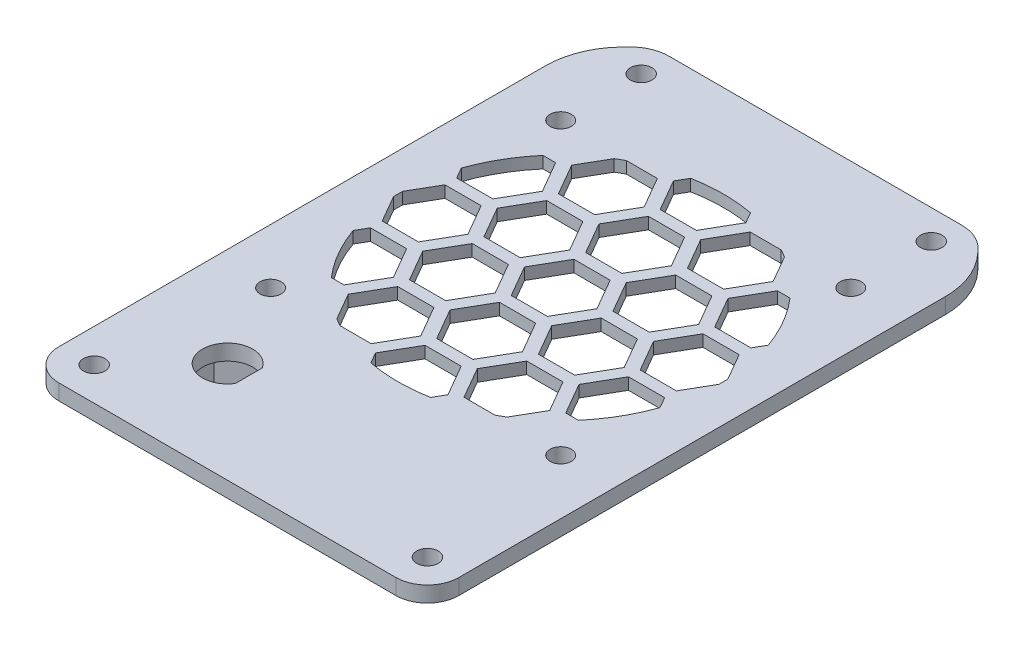
SolidWorks part; units mm, degrees
ref_plane "Front Plane" through (0, 0, 0) normal (0, 0, 1) x (1, 0, 0)
ref_plane "Top Plane" through (0, 0, 0) normal (0, 1, 0) x (1, 0, 0)
ref_plane "Right Plane" through (0, 0, 0) normal (1, 0, 0) x (0, 0, -1)
sketch "Sketch1" plane through (0, -8.5812, 0) normal (0, 1, 0) x (1, 0, 0)
  line L0 (-23.1823, 1.3362) -> (-42.1823, 1.3362)
  line L16 (-54.1823, -73.6638) -> (-11.1823, -73.6638)
  line L17 (-7.1823, -69.6638) -> (-7.1823, -7.6054)
  line L18 (-9.8717, -0.7822) -> (-11.849, 1.3362)
  line L19 (-11.849, 1.3362) -> (-23.1823, 1.3362)
  line L20 (-23.1823, 1.3362) -> (-23.1823, -1.1769)
  line L21 (-23.1823, -1.1769) -> (-10.589, -9.0704)
  line L22 (-9.1823, -11.6123) -> (-9.1823, -59.6638)
  line L23 (-9.1823, -59.6638) -> (-21.1823, -71.6638)
  line L24 (-21.1823, -71.6638) -> (-44.1823, -71.6638)
  line L25 (-44.1823, -71.6638) -> (-56.1823, -59.6638)
  line L26 (-56.1823, -59.6638) -> (-56.1823, -11.6123)
  line L27 (-54.7756, -9.0704) -> (-42.1823, -1.1769)
  line L28 (-42.1823, -1.1769) -> (-42.1823, 1.3362)
  line L29 (-42.1823, 1.3362) -> (-53.5156, 1.3362)
  line L30 (-53.5156, 1.3362) -> (-55.4928, -0.7822)
  line L31 (-58.1823, -7.6054) -> (-58.1823, -69.6638)
  line L32 (-54.1823, -73.6638) -> (-11.1823, -73.6638)
  line L33 (-7.1823, -69.6638) -> (-7.1823, -7.6054)
  line L34 (-9.8717, -0.7822) -> (-11.849, 1.3362)
  line L35 (-11.849, 1.3362) -> (-23.1823, 1.3362)
  line L36 (-23.1823, 1.3362) -> (-23.1823, -1.1769)
  line L37 (-23.1823, -1.1769) -> (-10.589, -9.0704)
  line L38 (-9.1823, -11.6123) -> (-9.1823, -59.6638)
  line L39 (-9.1823, -59.6638) -> (-21.1823, -71.6638)
  line L40 (-21.1823, -71.6638) -> (-44.1823, -71.6638)
  line L41 (-44.1823, -71.6638) -> (-56.1823, -59.6638)
  line L42 (-56.1823, -59.6638) -> (-56.1823, -11.6123)
  line L43 (-54.7756, -9.0704) -> (-42.1823, -1.1769)
  line L44 (-42.1823, -1.1769) -> (-42.1823, 1.3362)
  line L45 (-42.1823, 1.3362) -> (-53.5156, 1.3362)
  line L46 (-53.5156, 1.3362) -> (-55.4928, -0.7822)
  line L47 (-58.1823, -7.6054) -> (-58.1823, -69.6638)
  circle A0 centre (-14.1823, -2.3941) radius 1.375
  circle A1 centre (-51.1823, -2.3941) radius 1.375
  circle A2 centre (-11.4323, -69.4138) radius 1.375
  circle A3 centre (-53.9323, -69.4138) radius 1.375
  arc A6 (-11.1823, -73.6638) -> (-7.1823, -69.6638) centre (-11.1823, -69.6638) ccw
  arc A7 (-7.1823, -7.6054) -> (-9.8717, -0.7822) centre (-17.1823, -7.6054) ccw
  arc A8 (-9.1823, -11.6123) -> (-10.589, -9.0704) centre (-12.1823, -11.6123) ccw
  arc A9 (-54.7756, -9.0704) -> (-56.1823, -11.6123) centre (-53.1823, -11.6123) ccw
  arc A10 (-55.4928, -0.7822) -> (-58.1823, -7.6054) centre (-48.1823, -7.6054) ccw
  arc A11 (-58.1823, -69.6638) -> (-54.1823, -73.6638) centre (-54.1823, -69.6638) ccw
  arc A12 (-11.1823, -73.6638) -> (-7.1823, -69.6638) centre (-11.1823, -69.6638) ccw
  arc A13 (-7.1823, -7.6054) -> (-9.8717, -0.7822) centre (-17.1823, -7.6054) ccw
  arc A14 (-9.1823, -11.6123) -> (-10.589, -9.0704) centre (-12.1823, -11.6123) ccw
  arc A15 (-54.7756, -9.0704) -> (-56.1823, -11.6123) centre (-53.1823, -11.6123) ccw
  arc A16 (-55.4928, -0.7822) -> (-58.1823, -7.6054) centre (-48.1823, -7.6054) ccw
  arc A17 (-58.1823, -69.6638) -> (-54.1823, -73.6638) centre (-54.1823, -69.6638) ccw
  circle M24 centre (-51.1823, -2.3941) radius 2.3
  circle M25 centre (-11.4323, -69.4138) radius 2.3
  circle M26 centre (-53.9323, -69.4138) radius 2.3
  circle M27 centre (-14.1823, -2.3941) radius 2.3
  line M28 (-54.1823, -73.6638) -> (-11.1823, -73.6638)
  arc M29 (-11.1823, -73.6638) -> (-7.1823, -69.6638) centre (-11.1823, -69.6638) ccw
  line M30 (-7.1823, -69.6638) -> (-7.1823, -7.6054)
  arc M31 (-7.1823, -7.6054) -> (-9.8717, -0.7822) centre (-17.1823, -7.6054) ccw
  line M32 (-9.8717, -0.7822) -> (-11.849, 1.3362)
  line M33 (-11.849, 1.3362) -> (-23.1823, 1.3362)
  line M34 (-23.1823, 1.3362) -> (-23.1823, -1.1769)
  line M35 (-23.1823, -1.1769) -> (-10.589, -9.0704)
  arc M36 (-10.589, -9.0704) -> (-9.1823, -11.6123) centre (-12.1823, -11.6123) cw
  line M37 (-9.1823, -11.6123) -> (-9.1823, -59.6638)
  line M38 (-9.1823, -59.6638) -> (-21.1823, -71.6638)
  line M39 (-21.1823, -71.6638) -> (-44.1823, -71.6638)
  line M40 (-44.1823, -71.6638) -> (-56.1823, -59.6638)
  line M41 (-56.1823, -59.6638) -> (-56.1823, -11.6123)
  arc M42 (-56.1823, -11.6123) -> (-54.7756, -9.0704) centre (-53.1823, -11.6123) cw
  line M43 (-54.7756, -9.0704) -> (-42.1823, -1.1769)
  line M44 (-42.1823, -1.1769) -> (-42.1823, 1.3362)
  line M45 (-42.1823, 1.3362) -> (-53.5156, 1.3362)
  line M46 (-53.5156, 1.3362) -> (-55.4928, -0.7822)
  arc M47 (-55.4928, -0.7822) -> (-58.1823, -7.6054) centre (-48.1823, -7.6054) ccw
  line M48 (-58.1823, -7.6054) -> (-58.1823, -69.6638)
  arc M49 (-58.1823, -69.6638) -> (-54.1823, -73.6638) centre (-54.1823, -69.6638) ccw
  dimension "D2" = 2.75
  dimension "D3" = 2.75
  dimension "D4" = 2.75
  dimension "D5" = 2.75
  dimension "D1" = 0
extrude "Boss-Extrude1" add sketch "Sketch1" along normal blind 2 contours M49 M28 M29 M30 M31 M32 M33 M34 M35 M36 M37 M38 M39 M40 M41 M42 M43 M44 M45 M46 M47 M48 M25 M27 M26 M24 | L0 M34 M44 M43 M42 M41 M40 M39 M38 M37 M36 M35 | A0 M27 | A1 M24 | A3 M26 | A2 M25
fillet "Fillet1" radius 5 2 edges at (-11.849, -7.5812, -1.3362) (-53.5156, -7.5812, -1.3362)
sketch "Sketch2" plane through (0, -6.5812, 0) normal (0, 1, 0) x (1, 0, 0)
  circle A1 centre (-32.6823, -31.1638) radius 20.75
  circle A2 centre (-32.6823, -31.1638) radius 20.75
  dimension "D1" = 0
extrude "Cut-Extrude1" cut sketch "Sketch2" against normal through all
sketch "Sketch3" plane through (0, -8.5812, 0) normal (0, -1, 0) x (1, 0, 0)
  circle A2 centre (-32.6823, 31.1638) radius 21.75
  circle A3 centre (-32.6823, 31.1638) radius 21.75
  dimension "D1" = 1
extrude "Cut-Extrude2" cut sketch "Sketch3" against normal blind 0.5
sketch "Sketch4" plane through (0, -6.5812, 0) normal (0, 1, 0) x (1, 0, 0)
  line L0 (-49.1368, -12.1638) -> (-40.9095, -16.9138) construction
  line L1 (-38.6001, -12.9138) -> (-43.2189, -12.9138)
  line L2 (-43.2189, -12.9138) -> (-45.5283, -16.9138)
  line L3 (-45.5283, -16.9138) -> (-43.2189, -20.9138)
  line L4 (-43.2189, -20.9138) -> (-38.6001, -20.9138)
  line L5 (-38.6001, -20.9138) -> (-36.2907, -16.9138)
  line L6 (-36.2907, -16.9138) -> (-38.6001, -12.9138)
  line L7 (-44.518, -12.1638) -> (-46.8274, -8.1638)
  line L8 (-46.8274, -8.1638) -> (-51.4462, -8.1638)
  line L9 (-51.4462, -8.1638) -> (-53.7556, -12.1638)
  line L10 (-53.7556, -12.1638) -> (-51.4462, -16.1638)
  line L11 (-51.4462, -16.1638) -> (-46.8274, -16.1638)
  line L12 (-46.8274, -16.1638) -> (-44.518, -12.1638)
  line L13 (-22.1456, -12.9138) -> (-26.7644, -12.9138)
  line L14 (-26.7644, -12.9138) -> (-29.0738, -16.9138)
  line L15 (-29.0738, -16.9138) -> (-26.7644, -20.9138)
  line L16 (-26.7644, -20.9138) -> (-22.1456, -20.9138)
  line L17 (-22.1456, -20.9138) -> (-19.8362, -16.9138)
  line L18 (-19.8362, -16.9138) -> (-22.1456, -12.9138)
  line L19 (-28.0635, -12.1638) -> (-30.3729, -8.1638)
  line L20 (-34.9917, -8.1638) -> (-37.3011, -12.1638)
  line L21 (-37.3011, -12.1638) -> (-34.9917, -16.1638)
  line L22 (-34.9917, -16.1638) -> (-30.3729, -16.1638)
  line L23 (-30.3729, -16.1638) -> (-28.0635, -12.1638)
  line L24 (-32.6823, -12.1638) -> (-24.455, -16.9138) construction
  line L25 (-30.3729, -8.1638) -> (-34.9917, -8.1638)
  line L26 (-5.6912, -12.9138) -> (-10.31, -12.9138)
  line L27 (-10.31, -12.9138) -> (-12.6194, -16.9138)
  line L28 (-12.6194, -16.9138) -> (-10.31, -20.9138)
  line L29 (-10.31, -20.9138) -> (-5.6912, -20.9138)
  line L30 (-5.6912, -20.9138) -> (-3.3818, -16.9138)
  line L31 (-3.3818, -16.9138) -> (-5.6912, -12.9138)
  line L32 (-11.609, -12.1638) -> (-13.9184, -8.1638)
  line L33 (-18.5372, -8.1638) -> (-20.8466, -12.1638)
  line L34 (-20.8466, -12.1638) -> (-18.5372, -16.1638)
  line L35 (-18.5372, -16.1638) -> (-13.9184, -16.1638)
  line L36 (-13.9184, -16.1638) -> (-11.609, -12.1638)
  line L37 (-16.2278, -12.1638) -> (-8.0006, -16.9138) construction
  line L38 (-13.9184, -8.1638) -> (-18.5372, -8.1638)
  line L39 (-22.1456, -22.4138) -> (-26.7644, -22.4138)
  line L40 (-26.7644, -22.4138) -> (-29.0738, -26.4138)
  line L41 (-29.0738, -26.4138) -> (-26.7644, -30.4138)
  line L42 (-26.7644, -30.4138) -> (-22.1456, -30.4138)
  line L43 (-22.1456, -30.4138) -> (-19.8362, -26.4138)
  line L44 (-19.8362, -26.4138) -> (-22.1456, -22.4138)
  line L45 (-28.0635, -21.6638) -> (-30.3729, -17.6638)
  line L46 (-34.9917, -17.6638) -> (-37.3011, -21.6638)
  line L47 (-37.3011, -21.6638) -> (-34.9917, -25.6638)
  line L48 (-34.9917, -25.6638) -> (-30.3729, -25.6638)
  line L49 (-30.3729, -25.6638) -> (-28.0635, -21.6638)
  line L50 (-32.6823, -21.6638) -> (-24.455, -26.4138) construction
  line L51 (-30.3729, -17.6638) -> (-34.9917, -17.6638)
  line L52 (-5.6912, -22.4138) -> (-10.31, -22.4138)
  line L53 (-10.31, -22.4138) -> (-12.6194, -26.4138)
  line L54 (-12.6194, -26.4138) -> (-10.31, -30.4138)
  line L55 (-10.31, -30.4138) -> (-5.6912, -30.4138)
  line L56 (-5.6912, -30.4138) -> (-3.3818, -26.4138)
  line L57 (-3.3818, -26.4138) -> (-5.6912, -22.4138)
  line L58 (-11.609, -21.6638) -> (-13.9184, -17.6638)
  line L59 (-18.5372, -17.6638) -> (-20.8466, -21.6638)
  line L60 (-20.8466, -21.6638) -> (-18.5372, -25.6638)
  line L61 (-18.5372, -25.6638) -> (-13.9184, -25.6638)
  line L62 (-13.9184, -25.6638) -> (-11.609, -21.6638)
  line L63 (-16.2278, -21.6638) -> (-8.0006, -26.4138) construction
  line L64 (-13.9184, -17.6638) -> (-18.5372, -17.6638)
  line L65 (-22.1456, -31.9138) -> (-26.7644, -31.9138)
  line L66 (-26.7644, -31.9138) -> (-29.0738, -35.9138)
  line L67 (-29.0738, -35.9138) -> (-26.7644, -39.9138)
  line L68 (-26.7644, -39.9138) -> (-22.1456, -39.9138)
  line L69 (-22.1456, -39.9138) -> (-19.8362, -35.9138)
  line L70 (-19.8362, -35.9138) -> (-22.1456, -31.9138)
  line L71 (-28.0635, -31.1638) -> (-30.3729, -27.1638)
  line L72 (-34.9917, -27.1638) -> (-37.3011, -31.1638)
  line L73 (-37.3011, -31.1638) -> (-34.9917, -35.1638)
  line L74 (-34.9917, -35.1638) -> (-30.3729, -35.1638)
  line L75 (-30.3729, -35.1638) -> (-28.0635, -31.1638)
  line L76 (-32.6823, -31.1638) -> (-24.455, -35.9138) construction
  line L77 (-30.3729, -27.1638) -> (-34.9917, -27.1638)
  line L78 (-5.6912, -31.9138) -> (-10.31, -31.9138)
  line L79 (-10.31, -31.9138) -> (-12.6194, -35.9138)
  line L80 (-12.6194, -35.9138) -> (-10.31, -39.9138)
  line L81 (-10.31, -39.9138) -> (-5.6912, -39.9138)
  line L82 (-5.6912, -39.9138) -> (-3.3818, -35.9138)
  line L83 (-3.3818, -35.9138) -> (-5.6912, -31.9138)
  line L84 (-11.609, -31.1638) -> (-13.9184, -27.1638)
  line L85 (-18.5372, -27.1638) -> (-20.8466, -31.1638)
  line L86 (-20.8466, -31.1638) -> (-18.5372, -35.1638)
  line L87 (-18.5372, -35.1638) -> (-13.9184, -35.1638)
  line L88 (-13.9184, -35.1638) -> (-11.609, -31.1638)
  line L89 (-16.2278, -31.1638) -> (-8.0006, -35.9138) construction
  line L90 (-13.9184, -27.1638) -> (-18.5372, -27.1638)
  line L91 (-22.1456, -41.4138) -> (-26.7644, -41.4138)
  line L92 (-26.7644, -41.4138) -> (-29.0738, -45.4138)
  line L93 (-29.0738, -45.4138) -> (-26.7644, -49.4138)
  line L94 (-26.7644, -49.4138) -> (-22.1456, -49.4138)
  line L95 (-22.1456, -49.4138) -> (-19.8362, -45.4138)
  line L96 (-19.8362, -45.4138) -> (-22.1456, -41.4138)
  line L97 (-28.0635, -40.6638) -> (-30.3729, -36.6638)
  line L98 (-34.9917, -36.6638) -> (-37.3011, -40.6638)
  line L99 (-37.3011, -40.6638) -> (-34.9917, -44.6638)
  line L100 (-34.9917, -44.6638) -> (-30.3729, -44.6638)
  line L101 (-30.3729, -44.6638) -> (-28.0635, -40.6638)
  line L102 (-32.6823, -40.6638) -> (-24.455, -45.4138) construction
  line L103 (-30.3729, -36.6638) -> (-34.9917, -36.6638)
  line L104 (-5.6912, -41.4138) -> (-10.31, -41.4138)
  line L105 (-10.31, -41.4138) -> (-12.6194, -45.4138)
  line L106 (-12.6194, -45.4138) -> (-10.31, -49.4138)
  line L107 (-10.31, -49.4138) -> (-5.6912, -49.4138)
  line L108 (-5.6912, -49.4138) -> (-3.3818, -45.4138)
  line L109 (-3.3818, -45.4138) -> (-5.6912, -41.4138)
  line L110 (-11.609, -40.6638) -> (-13.9184, -36.6638)
  line L111 (-18.5372, -36.6638) -> (-20.8466, -40.6638)
  line L112 (-20.8466, -40.6638) -> (-18.5372, -44.6638)
  line L113 (-18.5372, -44.6638) -> (-13.9184, -44.6638)
  line L114 (-13.9184, -44.6638) -> (-11.609, -40.6638)
  line L115 (-16.2278, -40.6638) -> (-8.0006, -45.4138) construction
  line L116 (-13.9184, -36.6638) -> (-18.5372, -36.6638)
  line L117 (-22.1456, -50.9138) -> (-26.7644, -50.9138)
  line L118 (-26.7644, -50.9138) -> (-29.0738, -54.9138)
  line L119 (-29.0738, -54.9138) -> (-26.7644, -58.9138)
  line L120 (-26.7644, -58.9138) -> (-22.1456, -58.9138)
  line L121 (-22.1456, -58.9138) -> (-19.8362, -54.9138)
  line L122 (-19.8362, -54.9138) -> (-22.1456, -50.9138)
  line L123 (-28.0635, -50.1638) -> (-30.3729, -46.1638)
  line L124 (-34.9917, -46.1638) -> (-37.3011, -50.1638)
  line L125 (-37.3011, -50.1638) -> (-34.9917, -54.1638)
  line L126 (-34.9917, -54.1638) -> (-30.3729, -54.1638)
  line L127 (-30.3729, -54.1638) -> (-28.0635, -50.1638)
  line L128 (-32.6823, -50.1638) -> (-24.455, -54.9138) construction
  line L129 (-30.3729, -46.1638) -> (-34.9917, -46.1638)
  line L130 (-5.6912, -50.9138) -> (-10.31, -50.9138)
  line L131 (-10.31, -50.9138) -> (-12.6194, -54.9138)
  line L132 (-12.6194, -54.9138) -> (-10.31, -58.9138)
  line L133 (-10.31, -58.9138) -> (-5.6912, -58.9138)
  line L134 (-5.6912, -58.9138) -> (-3.3818, -54.9138)
  line L135 (-3.3818, -54.9138) -> (-5.6912, -50.9138)
  line L136 (-11.609, -50.1638) -> (-13.9184, -46.1638)
  line L137 (-18.5372, -46.1638) -> (-20.8466, -50.1638)
  line L138 (-20.8466, -50.1638) -> (-18.5372, -54.1638)
  line L139 (-18.5372, -54.1638) -> (-13.9184, -54.1638)
  line L140 (-13.9184, -54.1638) -> (-11.609, -50.1638)
  line L141 (-16.2278, -50.1638) -> (-8.0006, -54.9138) construction
  line L142 (-13.9184, -46.1638) -> (-18.5372, -46.1638)
  line L143 (-38.6001, -22.4138) -> (-43.2189, -22.4138)
  line L144 (-43.2189, -22.4138) -> (-45.5283, -26.4138)
  line L145 (-45.5283, -26.4138) -> (-43.2189, -30.4138)
  line L146 (-43.2189, -30.4138) -> (-38.6001, -30.4138)
  line L147 (-38.6001, -30.4138) -> (-36.2907, -26.4138)
  line L148 (-36.2907, -26.4138) -> (-38.6001, -22.4138)
  line L149 (-44.518, -21.6638) -> (-46.8274, -17.6638)
  line L150 (-51.4462, -17.6638) -> (-53.7556, -21.6638)
  line L151 (-53.7556, -21.6638) -> (-51.4462, -25.6638)
  line L152 (-51.4462, -25.6638) -> (-46.8274, -25.6638)
  line L153 (-46.8274, -25.6638) -> (-44.518, -21.6638)
  line L154 (-49.1368, -21.6638) -> (-40.9095, -26.4138) construction
  line L155 (-46.8274, -17.6638) -> (-51.4462, -17.6638)
  line L156 (-38.6001, -31.9138) -> (-43.2189, -31.9138)
  line L157 (-43.2189, -31.9138) -> (-45.5283, -35.9138)
  line L158 (-45.5283, -35.9138) -> (-43.2189, -39.9138)
  line L159 (-43.2189, -39.9138) -> (-38.6001, -39.9138)
  line L160 (-38.6001, -39.9138) -> (-36.2907, -35.9138)
  line L161 (-36.2907, -35.9138) -> (-38.6001, -31.9138)
  line L162 (-44.518, -31.1638) -> (-46.8274, -27.1638)
  line L163 (-51.4462, -27.1638) -> (-53.7556, -31.1638)
  line L164 (-53.7556, -31.1638) -> (-51.4462, -35.1638)
  line L165 (-51.4462, -35.1638) -> (-46.8274, -35.1638)
  line L166 (-46.8274, -35.1638) -> (-44.518, -31.1638)
  line L167 (-49.1368, -31.1638) -> (-40.9095, -35.9138) construction
  line L168 (-46.8274, -27.1638) -> (-51.4462, -27.1638)
  line L169 (-38.6001, -41.4138) -> (-43.2189, -41.4138)
  line L170 (-43.2189, -41.4138) -> (-45.5283, -45.4138)
  line L171 (-45.5283, -45.4138) -> (-43.2189, -49.4138)
  line L172 (-43.2189, -49.4138) -> (-38.6001, -49.4138)
  line L173 (-38.6001, -49.4138) -> (-36.2907, -45.4138)
  line L174 (-36.2907, -45.4138) -> (-38.6001, -41.4138)
  line L175 (-44.518, -40.6638) -> (-46.8274, -36.6638)
  line L176 (-51.4462, -36.6638) -> (-53.7556, -40.6638)
  line L177 (-53.7556, -40.6638) -> (-51.4462, -44.6638)
  line L178 (-51.4462, -44.6638) -> (-46.8274, -44.6638)
  line L179 (-46.8274, -44.6638) -> (-44.518, -40.6638)
  line L180 (-49.1368, -40.6638) -> (-40.9095, -45.4138) construction
  line L181 (-46.8274, -36.6638) -> (-51.4462, -36.6638)
  line L182 (-38.6001, -50.9138) -> (-43.2189, -50.9138)
  line L183 (-43.2189, -50.9138) -> (-45.5283, -54.9138)
  line L184 (-45.5283, -54.9138) -> (-43.2189, -58.9138)
  line L185 (-43.2189, -58.9138) -> (-38.6001, -58.9138)
  line L186 (-38.6001, -58.9138) -> (-36.2907, -54.9138)
  line L187 (-36.2907, -54.9138) -> (-38.6001, -50.9138)
  line L188 (-44.518, -50.1638) -> (-46.8274, -46.1638)
  line L189 (-51.4462, -46.1638) -> (-53.7556, -50.1638)
  line L190 (-53.7556, -50.1638) -> (-51.4462, -54.1638)
  line L191 (-51.4462, -54.1638) -> (-46.8274, -54.1638)
  line L192 (-46.8274, -54.1638) -> (-44.518, -50.1638)
  line L193 (-49.1368, -50.1638) -> (-40.9095, -54.9138) construction
  line L194 (-46.8274, -46.1638) -> (-51.4462, -46.1638)
  circle A0 centre (-40.9095, -16.9138) radius 4 construction
  circle A1 centre (-49.1368, -12.1638) radius 4 construction
  circle A2 centre (-24.455, -16.9138) radius 4 construction
  circle A3 centre (-32.6823, -12.1638) radius 4 construction
  circle A4 centre (-8.0006, -16.9138) radius 4 construction
  circle A5 centre (-16.2278, -12.1638) radius 4 construction
  circle A6 centre (-24.455, -26.4138) radius 4 construction
  circle A7 centre (-32.6823, -21.6638) radius 4 construction
  circle A8 centre (-8.0006, -26.4138) radius 4 construction
  circle A9 centre (-16.2278, -21.6638) radius 4 construction
  circle A10 centre (-24.455, -35.9138) radius 4 construction
  circle A11 centre (-32.6823, -31.1638) radius 4 construction
  circle A12 centre (-8.0006, -35.9138) radius 4 construction
  circle A13 centre (-16.2278, -31.1638) radius 4 construction
  circle A14 centre (-24.455, -45.4138) radius 4 construction
  circle A15 centre (-32.6823, -40.6638) radius 4 construction
  circle A16 centre (-8.0006, -45.4138) radius 4 construction
  circle A17 centre (-16.2278, -40.6638) radius 4 construction
  circle A18 centre (-24.455, -54.9138) radius 4 construction
  circle A19 centre (-32.6823, -50.1638) radius 4 construction
  circle A20 centre (-8.0006, -54.9138) radius 4 construction
  circle A21 centre (-16.2278, -50.1638) radius 4 construction
  circle A22 centre (-40.9095, -26.4138) radius 4 construction
  circle A23 centre (-49.1368, -21.6638) radius 4 construction
  circle A24 centre (-40.9095, -35.9138) radius 4 construction
  circle A25 centre (-49.1368, -31.1638) radius 4 construction
  circle A26 centre (-40.9095, -45.4138) radius 4 construction
  circle A27 centre (-49.1368, -40.6638) radius 4 construction
  circle A28 centre (-40.9095, -54.9138) radius 4 construction
  circle A29 centre (-49.1368, -50.1638) radius 4 construction
  circle A32 centre (-32.6823, -31.1638) radius 20.75
  point P21 (-40.9095, -20.9138)
  point P243 (-32.6823, -31.1638)
  circle M226 centre (-32.6823, -31.1638) radius 20.75
  dimension "D1" = 8
  dimension "D2" = 1.5
  dimension "D5" = 1.5
  dimension "D6" = 1.5
  dimension "D3" = 3
  dimension "D4" = 5
extrude "Boss-Extrude2" add sketch "Sketch4" against normal up to surface (1.5 mm away) contours L194 L188 L171 L170 L169 L174 L173 L172 L182 L187 L125 L124 L129 L123 L127 L118 L117 L94 L93 L92 L91 L96 L95 L137 L142 L113 L112 L111 L116 L110 L80 L79 L88 L87 L86 L85 L90 L84 L54 L53 M226 | L11 L12 M226 | L188 L194 M226 | L142 L137 M226 | L34 L35 M226 | L187 L182 M226 | L117 L118 M226 | L79 L80 M226 | L53 L54 M226 | A32
sketch "Sketch8" plane through (0, -6.5812, 0) normal (0, 1, 0) x (1, 0, 0)
  line L0 (-42.8661, -59.045) -> (-42.8661, -62.4801)
  circle A0 centre (-45.5661, -60.7626) radius 3.2
  dimension "D1" = 6.4
  dimension "D2" = 2.7
extrude "Cut-Extrude3" cut sketch "Sketch8" against normal through all contours L0 A0
sketch "Sketch9" plane through (0, -8.5812, 0) normal (0, -1, 0) x (1, 0, 0)
  line L0 (-42.8661, 59.045) -> (-42.8661, 62.4801) construction
  line L1 (-41.3911, 58.3522) -> (-41.3911, 63.173)
  line L2 (-41.3911, 63.173) -> (-45.5661, 65.5835)
  line L3 (-45.5661, 65.5835) -> (-49.7411, 63.173)
  line L4 (-49.7411, 63.173) -> (-49.7411, 58.3522)
  line L5 (-49.7411, 58.3522) -> (-45.5661, 55.9417)
  line L6 (-45.5661, 55.9417) -> (-41.3911, 58.3522)
  circle A0 centre (-45.5661, 60.7626) radius 4.175 construction
  circle A1 centre (-45.5661, 60.7626) radius 6
  dimension "D2" = 12
  dimension "D1" = 8.35
extrude "Boss-Extrude3" add sketch "Sketch9" along normal blind 5 contours A1 L6 L5 L4 L3 L2 L1
sketch "Sketch10" plane through (0, -6.5812, 0) normal (0, 1, 0) x (1, 0, 0)
  circle A0 centre (-14.1823, -49.6638) radius 1.5 construction
  circle A1 centre (-14.1823, -12.6638) radius 1.5 construction
  circle A2 centre (-51.1823, -12.6638) radius 1.5 construction
  circle A3 centre (-51.1823, -49.6638) radius 1.5 construction
  circle A4 centre (-14.1823, -49.6638) radius 1.5 construction
  circle A5 centre (-14.1823, -12.6638) radius 1.5 construction
  circle A6 centre (-51.1823, -12.6638) radius 1.5 construction
  circle A7 centre (-51.1823, -49.6638) radius 1.5 construction
  circle A8 centre (-14.1823, -49.6638) radius 1.35
  circle A9 centre (-51.1823, -49.6638) radius 1.35
  circle A10 centre (-51.1823, -12.6638) radius 1.35
  circle A11 centre (-14.1823, -12.6638) radius 1.35
  dimension "D1" = 2.7
  dimension "D2" = 2.7
  dimension "D3" = 2.7
  dimension "D4" = 2.7
extrude "Cut-Extrude4" cut sketch "Sketch10" against normal through all
